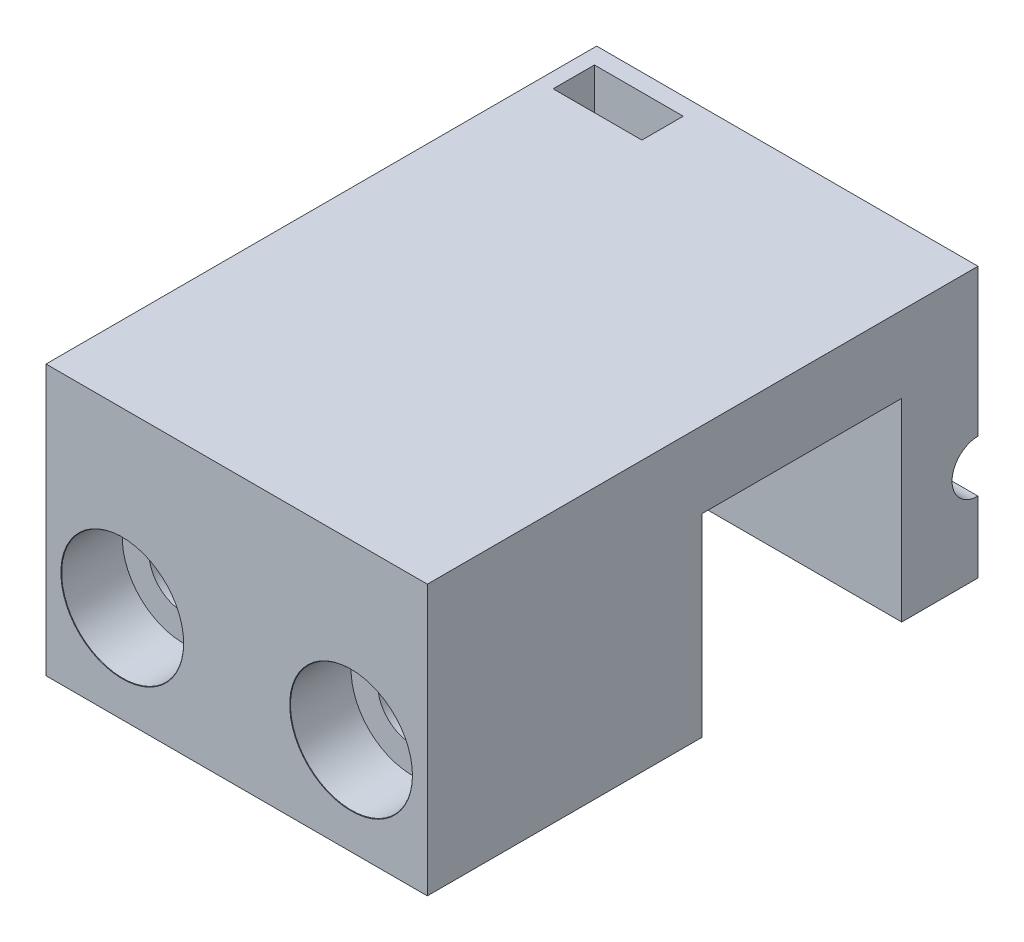
SolidWorks part; units mm, degrees
ref_plane "Front Plane" through (0, 0, 0) normal (0, 0, 1) x (1, 0, 0)
ref_plane "Top Plane" through (0, 0, 0) normal (0, 1, 0) x (1, 0, 0)
ref_plane "Right Plane" through (0, 0, 0) normal (1, 0, 0) x (0, 0, -1)
sketch "Sketch10" plane through (0, 0, 0) normal (0, 0, -1) x (-1, 0, 0)
  line L1 (-12.5, 6.35) -> (12.5, 6.35)
  line L2 (-12.5, 6.35) -> (-12.5, -6.35)
  line L3 (-12.5, -6.35) -> (12.5, -6.35)
  line L4 (12.5, 6.35) -> (12.5, -6.35)
  point P4 (-12.5, 0)
  point P6 (0, -6.35)
  dimension "D1" = 12.7
  dimension "D2" = 25
extrude "Boss-Extrude3" add sketch "Sketch10" against normal blind 18
hole_wizard "CBORE for M4 SHCS1" positions "Sketch16" profile "Sketch17" counterbore size "M4" standard "ANSI Metric" end condition through all
sketch "Sketch16" plane through (0, 0, 18) normal (0, 0, -1) x (-1, 0, 0)
  line L0 (-7.5, 0) -> (7.5, 0) construction
  point P0 (-7.5, 0)
  point P2 (7.5, 0)
  point P9 (0, 0)
  dimension "D1" = 15
sketch "Sketch17" plane through (7.5, 0, 18) normal (1, 0, 0) x (0, -1, 0)
  line L0 (0, 0) -> (0, 18)
  line L1 (0, 18) -> (2.25, 18)
  line L3 (2.25, 18) -> (2.25, 4)
  line L4 (4, 4) -> (2.25, 4)
  line L5 (4, 4) -> (4, 0.025)
  line L6 (4, 0.025) -> (4.025, 0)
  line L7 (4.025, 0) -> (0, 0)
  line L8 (-4, 0.025) -> (-4.025, 0) construction
  line L11 (0, -6.35) -> (0, 107.95) construction
  dimension "Thru Hole Dia." = 4.5
  dimension "Thru Hole Depth" = 18
  dimension "C'Bore Dia." = 8
  dimension "C'Bore Depth" = 4
  dimension "Near C'Sink Dia." = 8.05
  dimension "Near C'Sink Angle" = 90
sketch "Sketch19" plane through (0, 6.35, 0) normal (0, 1, 0) x (1, 0, 0)
  line L1 (-12.5, 0) -> (12.5, 0)
  line L2 (-12.5, 0) -> (-12.5, -18)
  line L3 (-12.5, -18) -> (12.5, -18)
  line L4 (12.5, 0) -> (12.5, -18)
extrude "Boss-Extrude6" add sketch "Sketch19" along normal blind 5
sketch "Sketch20" plane through (0, 0, 0) normal (0, 0, -1) x (-1, 0, 0)
  line L0 (12.5, -6.35) -> (12.5, 11.35) construction
  line L1 (-12.5, 11.35) -> (12.5, 11.35)
  line L2 (-12.5, 11.35) -> (-12.5, 6.35)
  line L3 (-12.5, 6.35) -> (12.5, 6.35)
  line L4 (12.5, 11.35) -> (12.5, 6.35)
  dimension "D1" = 5
extrude "Boss-Extrude7" add sketch "Sketch20" along normal blind 13.1
sketch "Sketch21" plane through (0, 0, -13.1) normal (0, 0, -1) x (-1, 0, 0)
  line L1 (-12.5, 11.35) -> (12.5, 11.35)
  line L2 (-12.5, 11.35) -> (-12.5, -6.35)
  line L3 (-12.5, -6.35) -> (12.5, -6.35)
  line L4 (12.5, 11.35) -> (12.5, -6.35)
extrude "Boss-Extrude8" add sketch "Sketch21" along normal blind 5
sketch "Sketch22" plane through (12.5, 0, 0) normal (1, 0, 0) x (0, 0, -1)
  line L0 (18.1, 11.35) -> (18.1, -6.35) construction
  arc A0 (18.1, 1.7) -> (18.1, -1.7) centre (18.1, 0) ccw
  point P3 (0, 0)
  point P7 (0, 0)
  dimension "D1" = 1.7
extrude "Cut-Extrude1" cut sketch "Sketch22" against normal blind 17.18 and the other way through all
hole_wizard "M3 Clearance Hole6" positions "Sketch23" profile "Sketch25" hole size "M3" standard "ANSI Metric"
sketch "Sketch23" plane through (0, 0, -18.1) normal (0, 0, -1) x (-1, 0, 0)
  line L0 (8.59, 4.025) -> (8.59, 0) construction
  line L1 (8.59, 0) -> (8.59, -4.025) construction
  line L3 (-12.5, -1.7) -> (-12.5, -6.35) construction
  line L4 (12.5, -1.7) -> (12.5, 1.7) construction
  point P0 (8.59, 4.025)
  point P26 (8.59, -4.025)
  point P38 (-12.5, -4.025)
  point P39 (0, 0)
  dimension "D1" = 3.91
sketch "Sketch25" plane through (-8.59, 4.025, -18.1) normal (1, 0, 0) x (0, 1, 0)
  line L0 (0, 0) -> (0, 6.0215)
  line L1 (0, 6.0215) -> (1.7, 5)
  line L2 (1.7, 5) -> (1.7, 0.025)
  line L3 (1.7, 0.025) -> (1.725, 0)
  line L5 (1.725, 0) -> (0, 0)
  line L6 (-1.7, 0.025) -> (-1.725, 0) construction
  line L10 (0, 6.0215) -> (-1.7, 5) construction
  line L11 (0, -6.35) -> (0, 107.95) construction
  dimension "Hole Dia." = 3.4
  dimension "Hole Depth" = 5
  dimension "Near C'Sink Dia." = 3.45
  dimension "Near C'Sink Angle" = 90
  dimension "Drill Angle" = 118
sketch "Sketch27" plane through (0, -6.35, 0) normal (0, -1, 0) x (1, 0, 0)
  line L0 (12.5, -18.1) -> (12.5, -13.1) construction
  line L1 (-11.5, -14.245) -> (-5.68, -14.245)
  line L2 (-11.5, -14.245) -> (-11.5, -16.955)
  line L3 (-11.5, -16.955) -> (-5.68, -16.955)
  line L4 (-5.68, -14.245) -> (-5.68, -16.955)
  line L5 (-12.5, -18.1) -> (-12.5, -13.1) construction
  point P4 (-5.68, -15.6)
  point P7 (12.5, -15.6)
  dimension "D1" = 5.82
  dimension "D2" = 2.71
  dimension "D3" = 1
extrude "Cut-Extrude2" cut sketch "Sketch27" against normal blind 5.82
sketch "Sketch28" plane through (0, 11.35, 11.35) normal (0, 1, 0) x (-1, 0, 0)
  line L1 (5.68, -25.595) -> (11.5, -25.595)
  line L2 (5.68, -25.595) -> (5.68, -28.305)
  line L3 (5.68, -28.305) -> (11.5, -28.305)
  line L4 (11.5, -25.595) -> (11.5, -28.305)
  line L7 (12.5, -29.45) -> (-12.5, -29.45) construction
  line L8 (12.5, -29.45) -> (12.5, 6.65) construction
  point P4 (11.5, -26.95)
  dimension "D1" = 5.82
  dimension "D2" = 2.71
  dimension "D3" = 2.5
  dimension "D4" = 1
extrude "Cut-Extrude3" cut sketch "Sketch28" against normal blind 10.82
